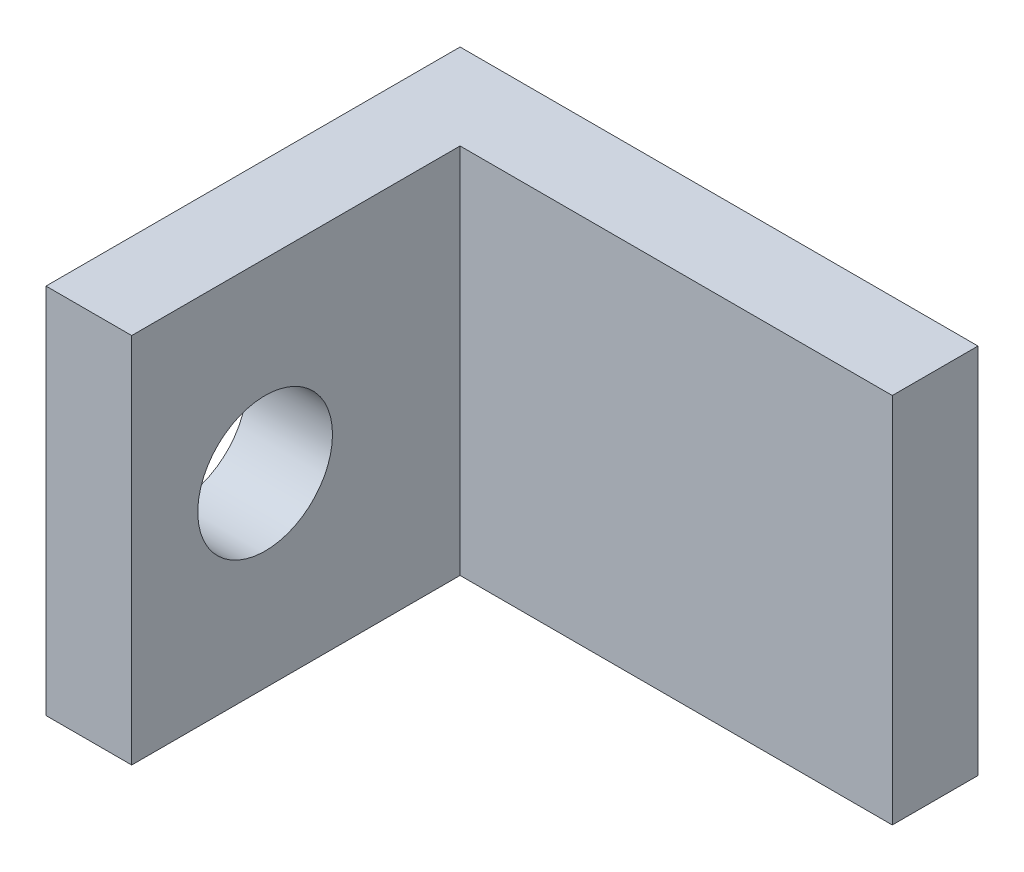
SolidWorks part; units mm, degrees
ref_plane "Front Plane" through (0, 0, 0) normal (0, 0, 1) x (1, 0, 0)
ref_plane "Top Plane" through (0, 0, 0) normal (0, 1, 0) x (1, 0, 0)
ref_plane "Right Plane" through (0, 0, 0) normal (1, 0, 0) x (0, 0, -1)
sketch "Sketch1" plane through (0, 0, 0) normal (0, 0, 1) x (1, 0, 0)
  line L0 (7.8718, -36.811) -> (7.8718, -15) construction
  line L1 (7.8718, -19.6707) -> (23.9095, -19.6707)
  line L2 (7.8718, -19.6707) -> (7.8718, -33.4727)
  line L3 (7.8718, -33.4727) -> (23.9095, -33.4727)
  line L4 (23.9095, -19.6707) -> (23.9095, -33.4727)
  line L5 (1.3364, -26.5717) -> (23.9095, -26.5717) construction
  circle A0 centre (30.5568, -26.5717) radius 2.5 construction
  dimension "D1" = 5
extrude "Boss-Extrude1" add sketch "Sketch1" against normal blind 3.18 from vertex at -3.18
sketch "Sketch3" plane through (7.8718, 0, 0) normal (-1, 0, 0) x (0, 0, 1)
  line L1 (-6.36, -33.4727) -> (9.0041, -33.4727)
  line L2 (-6.36, -33.4727) -> (-6.36, -19.6707)
  line L3 (-6.36, -19.6707) -> (9.0041, -19.6707)
  line L4 (9.0041, -33.4727) -> (9.0041, -19.6707)
  line L5 (9.0041, -26.5717) -> (4.0537, -26.5717) construction
  circle A1 centre (4.0537, -26.5717) radius 2.5
  dimension "D1" = 5
extrude "Boss-Extrude2" add sketch "Sketch3" along normal blind 3.18
